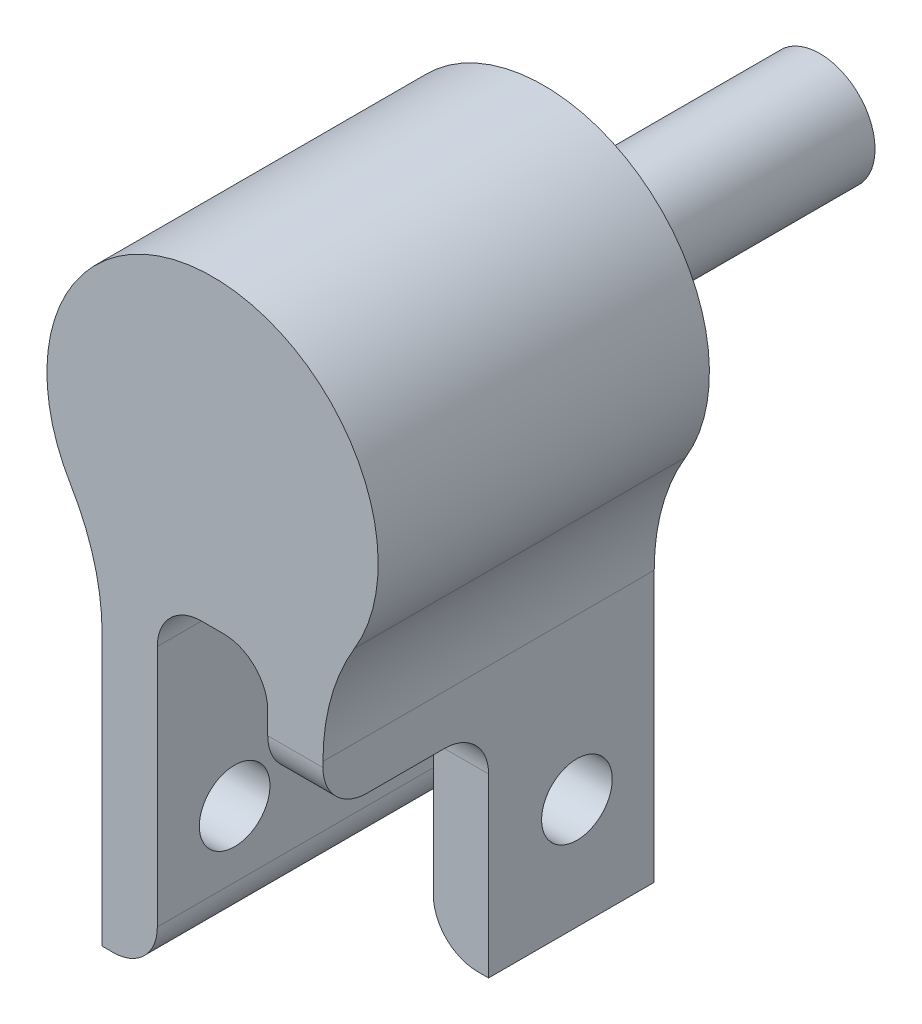
SolidWorks part; units mm, degrees
material "PUR"
ref_plane "Front Plane" through (0, 0, 0) normal (0, 0, 1) x (1, 0, 0)
ref_plane "Top Plane" through (0, 0, 0) normal (0, 1, 0) x (1, 0, 0)
ref_plane "Right Plane" through (0, 0, 0) normal (1, 0, 0) x (0, 0, -1)
sketch "Sketch2" plane through (0, 0, 0) normal (0, 0, 1) x (1, 0, 0)
  line L8 (0, 0) -> (0, -6.2546) construction
  line L9 (0, -6.2546) -> (0, -21.2546) construction
  line L10 (-2.5, -6.2546) -> (-2.5, -21.2546)
  line L11 (2.5, -6.2546) -> (2.5, -21.2546)
  line L12 (-5, -6.2546) -> (-5, -21.2546)
  line L13 (5, -6.2546) -> (5, -21.2546)
  line L14 (-5, -6.2546) -> (-5, -5.5902)
  line L15 (5, -6.2546) -> (5, -5.5902)
  line L16 (-2.5, -6.2546) -> (2.5, -6.2546)
  line L17 (-5, -21.2546) -> (-2.5, -21.2546)
  line L18 (2.5, -21.2546) -> (5, -21.2546)
  arc A0 (5, -5.5902) -> (-5, -5.5902) centre (0, 0) ccw
  dimension "D1" = 2.5
  dimension "D3" = 15
  dimension "D2" = 2.5
  dimension "D4" = 5
  dimension "D5" = 5
  dimension "D6" = 15
extrude "Boss-Extrude1" add sketch "Sketch2" along normal blind 15
sketch "Sketch3" plane through (0, 0, 0) normal (0, 0, -1) x (-1, 0, 0)
  circle A0 centre (0, 0) radius 2.5
  dimension "D1" = 5
fillet "Fillet1" radius 10 2 edges at (5, -5.5902, 7.5) (-5, -5.5902, 7.5)
extrude "Boss-Extrude2" add sketch "Sketch3" along normal blind 12.5
sketch "Sketch7" plane through (5, 0, 0) normal (1, 0, 0) x (0, 0, -1)
  line L1 (-15, -21.2546) -> (-7.5, -21.2546)
  line L2 (-15, -21.2546) -> (-15, -11.2546)
  line L3 (-15, -11.2546) -> (-7.5, -11.2546)
  line L4 (-7.5, -21.2546) -> (-7.5, -11.2546)
  dimension "D1" = 10
  dimension "D2" = 7.5
extrude "Cut-Extrude4" cut sketch "Sketch7" against normal up to next
sketch "Sketch9" plane through (-5, 0, 0) normal (-1, 0, 0) x (0, 0, 1)
  line L0 (0, -9.0139) -> (0, -21.2546) construction
  line L1 (15, -21.2546) -> (0, -21.2546) construction
  circle A0 centre (3.5, -16.2546) radius 1.6
  dimension "D1" = 3.2
  dimension "D2" = 3.5
  dimension "D3" = 5
sketch "Sketch10" plane through (-5, 0, 0) normal (-1, 0, 0) x (0, 0, 1)
  line L0 (15, -21.2546) -> (0, -21.2546) construction
  line L1 (15, -9.0139) -> (15, -21.2546) construction
  circle A0 centre (11.5, -16.2546) radius 1.6
  dimension "D1" = 3.2
  dimension "D2" = 5
  dimension "D3" = 3.5
extrude "Cut-Extrude7" cut sketch "Sketch10" against normal up to next
extrude "Cut-Extrude8" cut sketch "Sketch9" against normal through all
fillet "Fillet2" radius 2 4 edges at (2.5, -21.2546, 3.75) (-2.5, -21.2546, 7.5) (2.5, -6.2546, 7.5) (-2.5, -6.2546, 7.5)
fillet "Fillet3" radius 1 1 edges at (-2.5, 0, 0)
fillet "Fillet4" radius 2 2 edges at (3.75, -11.2546, 15) (3.75, -11.2546, 7.5)
